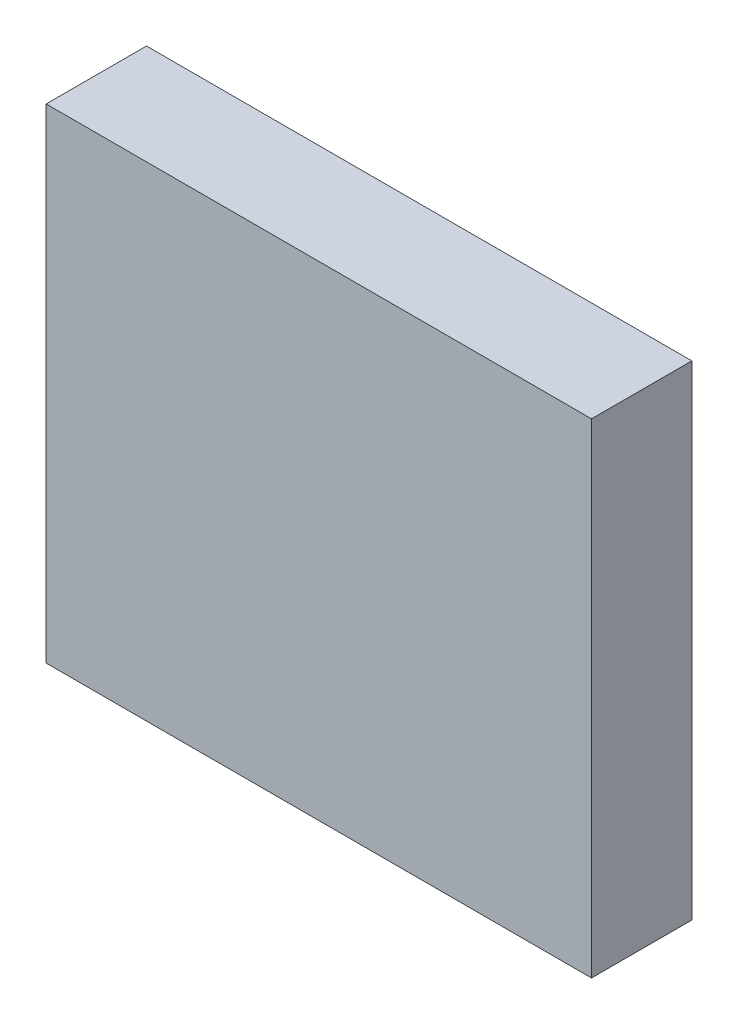
SolidWorks part; units mm, degrees
ref_plane "正面" through (0, 0, 0) normal (0, 0, 1) x (1, 0, 0)
ref_plane "平面" through (0, 0, 0) normal (0, 1, 0) x (1, 0, 0)
ref_plane "右側面" through (0, 0, 0) normal (1, 0, 0) x (0, 0, -1)
sketch "ｽｹｯﾁ1" plane through (0, 0, 0) normal (0, 0, 1) x (1, 0, 0)
  line L0 (-45, 0) -> (45, 0) construction
  line L1 (-45, 45) -> (45, 45)
  line L2 (-45, 45) -> (-45, -45)
  line L3 (-45, -45) -> (45, -45)
  line L4 (45, 45) -> (45, -45)
  line L5 (0, -45) -> (0, 45) construction
  point P8 (0, 0)
  dimension "D1" = 90
  dimension "D2" = 90
  dimension "D3" = 0
  dimension "D4" = 0
extrude "ﾎﾞｽ - 押し出し1" add sketch "ｽｹｯﾁ1" along normal blind 1.6
sketch "ｽｹｯﾁ4" plane through (0, 0, 0) normal (0, 0, -1) x (-1, 0, 0)
  line L0 (-45, -45) -> (-45, 45) construction
  line L1 (-23.89, -36.1) -> (-6.11, -36.1)
  line L2 (-23.89, -36.1) -> (-23.89, -44.6)
  line L3 (-23.89, -44.6) -> (-6.11, -44.6)
  line L4 (-6.11, -36.1) -> (-6.11, -44.6)
  line L6 (45, 45) -> (45, -45) construction
  line L8 (-38.85, 26.89) -> (-36.35, 26.89)
  line L9 (-38.85, 26.89) -> (-38.85, 9.11)
  line L10 (-38.85, 9.11) -> (-36.35, 9.11)
  line L11 (-36.35, 26.89) -> (-36.35, 9.11)
  line L12 (16.11, 44.6) -> (33.89, 44.6)
  line L13 (16.11, 44.6) -> (16.11, 36.1)
  line L14 (16.11, 36.1) -> (33.89, 36.1)
  line L15 (33.89, 44.6) -> (33.89, 36.1)
  line L16 (-45, 45) -> (45, 45) construction
  line L17 (45, -45) -> (-45, -45) construction
  line L18 (36.1, 26.89) -> (44.6, 26.89)
  line L19 (36.1, 26.89) -> (36.1, 9.11)
  line L20 (36.1, 9.11) -> (44.6, 9.11)
  line L21 (44.6, 26.89) -> (44.6, 9.11)
  point P6 (25, 44.6)
  point P7 (-15, -44.6)
  point P14 (-38.85, 18)
  point P15 (-37.6, 9.11)
  point P25 (44.6, 18)
  dimension "D2" = 8.5
  dimension "D3" = 8.5
  dimension "D4" = 17.78
  dimension "D5" = 2.5
  dimension "D6" = 17.78
  dimension "D7" = 27
  dimension "D8" = 7.4
  dimension "D9" = 20
  dimension "D10" = 30
  dimension "D11" = 0.4
  dimension "D12" = 17.78
  dimension "D13" = 17.78
  dimension "D14" = 0.4
  dimension "D15" = 27
  dimension "D16" = 8.5
  dimension "D17" = 0.4
extrude "ﾎﾞｽ - 押し出し2" add sketch "ｽｹｯﾁ4" along normal blind 2.5
sketch "ｽｹｯﾁ5" plane through (0, 0, -2.5) normal (0, 0, -1) x (-1, 0, 0)
  line L8 (-38.85, 9.11) -> (-36.35, 9.11) construction
  line L33 (-37.92, 18.32) -> (-37.28, 18.32)
  line L34 (-37.92, 18.32) -> (-37.92, 17.68)
  line L35 (-37.92, 17.68) -> (-37.28, 17.68)
  line L36 (-37.28, 18.32) -> (-37.28, 17.68)
  line L37 (-38.85, 26.89) -> (-38.85, 9.11) construction
  line L39 (-37.92, 15.78) -> (-37.28, 15.78)
  line L40 (-37.92, 15.78) -> (-37.92, 15.14)
  line L41 (-37.92, 15.14) -> (-37.28, 15.14)
  line L42 (-37.28, 15.78) -> (-37.28, 15.14)
  line L45 (-37.92, 13.24) -> (-37.28, 13.24)
  line L46 (-37.92, 13.24) -> (-37.92, 12.6)
  line L47 (-37.92, 12.6) -> (-37.28, 12.6)
  line L48 (-37.28, 13.24) -> (-37.28, 12.6)
  line L49 (-37.92, 10.7) -> (-37.28, 10.7)
  line L50 (-37.92, 10.7) -> (-37.92, 10.06)
  line L51 (-37.92, 10.06) -> (-37.28, 10.06)
  line L52 (-37.28, 10.7) -> (-37.28, 10.06)
  line L53 (-37.92, 20.86) -> (-37.28, 20.86)
  line L54 (-37.92, 20.86) -> (-37.92, 20.22)
  line L55 (-37.92, 20.22) -> (-37.28, 20.22)
  line L56 (-37.28, 20.86) -> (-37.28, 20.22)
  line L57 (-37.92, 23.4) -> (-37.28, 23.4)
  line L58 (-37.92, 23.4) -> (-37.92, 22.76)
  line L59 (-37.92, 22.76) -> (-37.28, 22.76)
  line L60 (-37.28, 23.4) -> (-37.28, 22.76)
  line L61 (-37.92, 25.94) -> (-37.28, 25.94)
  line L62 (-37.92, 25.94) -> (-37.92, 25.3)
  line L63 (-37.92, 25.3) -> (-37.28, 25.3)
  line L64 (-37.28, 25.94) -> (-37.28, 25.3)
  point P47 (-37.6, 17.68)
  point P50 (-37.6, 9.11)
  point P53 (-37.92, 18)
  point P54 (-38.85, 18)
  point P59 (-37.28, 15.46)
  point P60 (-37.28, 18)
  point P61 (-37.28, 12.92)
  point P70 (-37.28, 10.38)
  point P83 (-37.28, 20.54)
  point P84 (-37.28, 23.08)
  point P85 (-37.28, 25.62)
  point P179 (-37.6, 10.7)
  point P180 (-37.6, 13.24)
  point P181 (-37.6, 15.78)
  point P182 (-37.6, 18.32)
  point P183 (-37.6, 20.86)
  point P184 (-37.6, 23.4)
  point P185 (-37.6, 25.94)
  dimension "D21" = 0.64
  dimension "D22" = 0.64
  dimension "D23" = 0.64
  dimension "D24" = 0.64
  dimension "D25" = 2.54
  dimension "D26" = 0.64
  dimension "D27" = 2.54
  dimension "D28" = 0.64
  dimension "D29" = 2.54
  dimension "D30" = 0.64
  dimension "D31" = 0.64
  dimension "D32" = 0.64
  dimension "D33" = 0.64
  dimension "D34" = 2.54
  dimension "D35" = 2.54
  dimension "D36" = 0.64
  dimension "D37" = 0.64
  dimension "D38" = 0.64
  dimension "D39" = 2.54
  dimension "D40" = 0.64
extrude "ﾎﾞｽ - 押し出し3" add sketch "ｽｹｯﾁ5" along normal blind 6.1
sketch "ｽｹｯﾁ6" plane through (0, 0, 1.6) normal (0, 0, 1) x (1, 0, 0)
  line L0 (-45, -45) -> (45, -45) construction
  line L1 (-41.74, -33.26) -> (-38.26, -33.26)
  line L2 (-41.74, -33.26) -> (-41.74, -36.74)
  line L3 (-41.74, -36.74) -> (-38.26, -36.74)
  line L4 (-38.26, -33.26) -> (-38.26, -36.74)
  line L5 (-45, 45) -> (-45, -45) construction
  line L6 (45, 45) -> (-45, 45) construction
  line L7 (-41.74, 36.74) -> (-38.26, 36.74)
  line L8 (-41.74, 36.74) -> (-41.74, 33.26)
  line L9 (-41.74, 33.26) -> (-38.26, 33.26)
  line L10 (-38.26, 36.74) -> (-38.26, 33.26)
  line L11 (45, -45) -> (45, 45) construction
  line L12 (28.26, -33.26) -> (31.74, -33.26)
  line L13 (28.26, -33.26) -> (28.26, -36.74)
  line L14 (28.26, -36.74) -> (31.74, -36.74)
  line L15 (31.74, -33.26) -> (31.74, -36.74)
  line L17 (28.26, 36.74) -> (31.74, 36.74)
  line L18 (28.26, 36.74) -> (28.26, 33.26)
  line L19 (28.26, 33.26) -> (31.74, 33.26)
  line L20 (31.74, 36.74) -> (31.74, 33.26)
  point P4 (-41.74, -35)
  point P7 (-40, -36.74)
  point P14 (-41.74, 35)
  point P17 (-40, 36.74)
  point P22 (30, -36.74)
  point P25 (31.74, -35)
  point P30 (30, 36.74)
  point P31 (31.74, 35)
  dimension "D1" = 3.48
  dimension "D2" = 3.48
  dimension "D3" = 10
  dimension "D4" = 5
  dimension "D5" = 3.48
  dimension "D6" = 3.48
  dimension "D7" = 10
  dimension "D8" = 5
  dimension "D9" = 15
  dimension "D10" = 10
  dimension "D11" = 3.48
  dimension "D12" = 3.48
  dimension "D13" = 15
  dimension "D14" = 10
  dimension "D15" = 3.48
  dimension "D16" = 3.48
extrude "ﾎﾞｽ - 押し出し4" add sketch "ｽｹｯﾁ6" along normal blind 2
sketch "ｽｹｯﾁ7" plane through (0, 0, 1.6) normal (0, 0, 1) x (1, 0, 0)
  line L0 (-45, -45) -> (45, -45) construction
  line L1 (-41, 2) -> (-39, 2)
  line L2 (-41, 2) -> (-41, -2)
  line L3 (-41, -2) -> (-39, -2)
  line L4 (-39, 2) -> (-39, -2)
  line L5 (-45, 45) -> (-45, -45) construction
  line L6 (45, -45) -> (45, 45) construction
  line L7 (29, 2) -> (31, 2)
  line L8 (29, 2) -> (29, -2)
  line L9 (29, -2) -> (31, -2)
  line L10 (31, 2) -> (31, -2)
  line L11 (45, 45) -> (-45, 45) construction
  line L12 (-7, 36) -> (-3, 36)
  line L13 (-7, 36) -> (-7, 34)
  line L14 (-7, 34) -> (-3, 34)
  line L15 (-3, 36) -> (-3, 34)
  line L17 (-7, -34) -> (-3, -34)
  line L18 (-7, -34) -> (-7, -36)
  line L19 (-7, -36) -> (-3, -36)
  line L20 (-3, -34) -> (-3, -36)
  line L21 (-6, 2) -> (-4, 2)
  line L22 (-6, 2) -> (-6, -2)
  line L23 (-6, -2) -> (-4, -2)
  line L24 (-4, 2) -> (-4, -2)
  point P4 (-41, 0)
  point P7 (-40, -2)
  point P14 (30, 2)
  point P17 (31, 0)
  point P22 (-7, 35)
  point P25 (-5, 36)
  point P30 (-7, -35)
  point P31 (-5, -36)
  point P36 (-4, 0)
  point P37 (29, 0)
  point P38 (-5, 34)
  point P39 (-5, 2)
  dimension "D1" = 4
  dimension "D2" = 2
  dimension "D3" = 45
  dimension "D4" = 5
  dimension "D5" = 4
  dimension "D6" = 2
  dimension "D7" = 15
  dimension "D8" = 45
  dimension "D9" = 4
  dimension "D10" = 2
  dimension "D11" = 10
  dimension "D12" = 40
  dimension "D13" = 4
  dimension "D14" = 2
  dimension "D15" = 10
  dimension "D16" = 40
  dimension "D17" = 4
  dimension "D18" = 2
extrude "ﾎﾞｽ - 押し出し5" add sketch "ｽｹｯﾁ7" along normal blind 1.1
sketch "ｽｹｯﾁ8" plane through (0, 0, 1.6) normal (0, 0, 1) x (1, 0, 0)
  line L1 (7.3, 7.6) -> (14.7, 7.6)
  line L2 (7.3, 7.6) -> (7.3, -7.6)
  line L3 (7.3, -7.6) -> (14.7, -7.6)
  line L4 (14.7, 7.6) -> (14.7, -7.6)
  line L5 (-45, 45) -> (-45, -45) construction
  point P4 (7.3, 0)
  point P11 (-45, 0)
  point P12 (11, 7.6)
  dimension "D1" = 15.2
  dimension "D2" = 7.4
  dimension "D3" = 56
extrude "ﾎﾞｽ - 押し出し6" add sketch "ｽｹｯﾁ8" along normal blind 2.65
sketch "ｽｹｯﾁ9" plane through (0, -44.6, 0) normal (0, -1, 0) x (1, 0, 0)
  line L1 (14.68, -0.93) -> (15.32, -0.93)
  line L2 (14.68, -0.93) -> (14.68, -1.57)
  line L3 (14.68, -1.57) -> (15.32, -1.57)
  line L4 (15.32, -0.93) -> (15.32, -1.57)
  line L5 (6.11, -2.5) -> (6.11, 0) construction
  line L6 (6.11, -1.25) -> (23.89, -1.25) construction
  line L7 (23.89, -2.5) -> (23.89, 0) construction
  line L8 (23.89, -2.5) -> (6.11, -2.5) construction
  line L10 (15, -2.5) -> (15, 0) construction
  line L11 (23.89, 0) -> (6.11, 0) construction
  line L13 (12.14, -0.93) -> (12.78, -0.93)
  line L14 (12.14, -0.93) -> (12.14, -1.57)
  line L15 (12.14, -1.57) -> (12.78, -1.57)
  line L16 (12.78, -0.93) -> (12.78, -1.57)
  line L17 (9.6, -0.93) -> (10.24, -0.93)
  line L18 (9.6, -0.93) -> (9.6, -1.57)
  line L19 (9.6, -1.57) -> (10.24, -1.57)
  line L20 (10.24, -0.93) -> (10.24, -1.57)
  line L21 (7.06, -0.93) -> (7.7, -0.93)
  line L22 (7.06, -0.93) -> (7.06, -1.57)
  line L23 (7.06, -1.57) -> (7.7, -1.57)
  line L24 (7.7, -0.93) -> (7.7, -1.57)
  line L25 (17.22, -0.93) -> (17.86, -0.93)
  line L26 (17.22, -0.93) -> (17.22, -1.57)
  line L27 (17.22, -1.57) -> (17.86, -1.57)
  line L28 (17.86, -0.93) -> (17.86, -1.57)
  line L29 (19.76, -0.93) -> (20.4, -0.93)
  line L30 (19.76, -0.93) -> (19.76, -1.57)
  line L31 (19.76, -1.57) -> (20.4, -1.57)
  line L32 (20.4, -0.93) -> (20.4, -1.57)
  line L33 (22.3, -0.93) -> (22.94, -0.93)
  line L34 (22.3, -0.93) -> (22.3, -1.57)
  line L35 (22.3, -1.57) -> (22.94, -1.57)
  line L36 (22.94, -0.93) -> (22.94, -1.57)
  point P10 (15.32, -1.25)
  point P13 (15, -1.57)
  point P42 (12.46, -1.57)
  point P43 (9.92, -1.57)
  point P44 (12.14, -1.25)
  point P46 (9.6, -1.25)
  point P47 (7.06, -1.25)
  point P48 (7.38, -1.57)
  point P49 (17.54, -1.57)
  point P50 (20.08, -1.57)
  point P51 (22.62, -1.57)
  point P52 (17.22, -1.25)
  point P53 (19.76, -1.25)
  point P54 (22.3, -1.25)
  dimension "D1" = 0.64
  dimension "D2" = 0.64
  dimension "D3" = 0.64
  dimension "D4" = 0.64
  dimension "D5" = 0.64
  dimension "D6" = 0.64
  dimension "D7" = 0.64
  dimension "D8" = 0.64
  dimension "D9" = 0.64
  dimension "D10" = 0.64
  dimension "D11" = 0.64
  dimension "D12" = 2.54
  dimension "D13" = 2.54
  dimension "D14" = 2.54
  dimension "D15" = 0.64
  dimension "D16" = 0.64
  dimension "D17" = 0.64
  dimension "D18" = 2.54
  dimension "D19" = 2.54
  dimension "D20" = 2.54
extrude "ｶｯﾄ - 押し出し1" cut sketch "ｽｹｯﾁ9" against normal blind 7.5
sketch "ｽｹｯﾁ10" plane through (-44.6, 0, 0) normal (-1, 0, 0) x (0, 0, 1)
  line L0 (-1.25, 26.89) -> (-1.25, 9.11) construction
  line L1 (-2.5, 26.89) -> (0, 26.89) construction
  line L2 (-2.5, 9.11) -> (0, 9.11) construction
  line L3 (-2.5, 18) -> (0, 18) construction
  line L4 (-2.5, 9.11) -> (-2.5, 26.89) construction
  line L5 (0, 9.11) -> (0, 26.89) construction
  line L7 (-1.57, 18.32) -> (-0.93, 18.32)
  line L8 (-1.57, 18.32) -> (-1.57, 17.68)
  line L9 (-1.57, 17.68) -> (-0.93, 17.68)
  line L10 (-0.93, 18.32) -> (-0.93, 17.68)
  line L11 (-1.57, 25.94) -> (-0.93, 25.94)
  line L12 (-1.57, 25.94) -> (-1.57, 25.3)
  line L13 (-1.57, 25.3) -> (-0.93, 25.3)
  line L14 (-0.93, 25.94) -> (-0.93, 25.3)
  line L15 (-1.57, 23.4) -> (-0.93, 23.4)
  line L16 (-1.57, 23.4) -> (-1.57, 22.76)
  line L17 (-1.57, 22.76) -> (-0.93, 22.76)
  line L18 (-0.93, 23.4) -> (-0.93, 22.76)
  line L19 (-1.57, 20.86) -> (-0.93, 20.86)
  line L20 (-1.57, 20.86) -> (-1.57, 20.22)
  line L21 (-1.57, 20.22) -> (-0.93, 20.22)
  line L22 (-0.93, 20.86) -> (-0.93, 20.22)
  line L23 (-1.57, 15.78) -> (-0.93, 15.78)
  line L24 (-1.57, 15.78) -> (-1.57, 15.14)
  line L25 (-1.57, 15.14) -> (-0.93, 15.14)
  line L26 (-0.93, 15.78) -> (-0.93, 15.14)
  line L27 (-1.57, 13.24) -> (-0.93, 13.24)
  line L28 (-1.57, 13.24) -> (-1.57, 12.6)
  line L29 (-1.57, 12.6) -> (-0.93, 12.6)
  line L30 (-0.93, 13.24) -> (-0.93, 12.6)
  line L31 (-1.57, 10.7) -> (-0.93, 10.7)
  line L32 (-1.57, 10.7) -> (-1.57, 10.06)
  line L33 (-1.57, 10.06) -> (-0.93, 10.06)
  line L34 (-0.93, 10.7) -> (-0.93, 10.06)
  point P16 (-1.25, 18.32)
  point P17 (-1.57, 18)
  point P30 (-1.57, 20.54)
  point P31 (-0.93, 23.08)
  point P32 (-0.93, 20.54)
  point P33 (-0.93, 25.62)
  point P34 (-1.25, 20.86)
  point P35 (-1.25, 23.4)
  point P36 (-1.25, 25.94)
  point P49 (-0.93, 15.46)
  point P50 (-0.93, 12.92)
  point P51 (-0.93, 10.38)
  dimension "D1" = 0.64
  dimension "D2" = 0.64
  dimension "D3" = 0.64
  dimension "D4" = 0.64
  dimension "D5" = 0.64
  dimension "D6" = 2.54
  dimension "D7" = 2.54
  dimension "D8" = 2.54
  dimension "D9" = 0.64
  dimension "D10" = 0.64
  dimension "D11" = 0.64
  dimension "D12" = 0.64
  dimension "D13" = 0.64
  dimension "D14" = 0.64
  dimension "D15" = 2.54
  dimension "D16" = 2.54
  dimension "D17" = 2.54
  dimension "D18" = 0.64
  dimension "D19" = 0.64
  dimension "D20" = 0.64
extrude "ｶｯﾄ - 押し出し2" cut sketch "ｽｹｯﾁ10" against normal blind 7.5
sketch "ｽｹｯﾁ11" plane through (0, 44.6, 0) normal (0, 1, 0) x (1, 0, 0)
  line L0 (-33.89, 1.25) -> (-16.11, 1.25) construction
  line L1 (-33.89, 2.5) -> (-33.89, 0) construction
  line L2 (-16.11, 2.5) -> (-16.11, 0) construction
  line L3 (-25, 2.5) -> (-25, 0) construction
  line L4 (-33.89, 2.5) -> (-16.11, 2.5) construction
  line L5 (45, 0) -> (-45, 0) construction
  line L7 (-25.32, 1.57) -> (-24.68, 1.57)
  line L8 (-25.32, 1.57) -> (-25.32, 0.93)
  line L9 (-25.32, 0.93) -> (-24.68, 0.93)
  line L10 (-24.68, 1.57) -> (-24.68, 0.93)
  line L11 (-32.94, 1.57) -> (-32.3, 1.57)
  line L12 (-32.94, 1.57) -> (-32.94, 0.93)
  line L13 (-32.94, 0.93) -> (-32.3, 0.93)
  line L14 (-32.3, 1.57) -> (-32.3, 0.93)
  line L15 (-30.4, 1.57) -> (-29.76, 1.57)
  line L16 (-30.4, 1.57) -> (-30.4, 0.93)
  line L17 (-30.4, 0.93) -> (-29.76, 0.93)
  line L18 (-29.76, 1.57) -> (-29.76, 0.93)
  line L19 (-27.86, 1.57) -> (-27.22, 1.57)
  line L20 (-27.86, 1.57) -> (-27.86, 0.93)
  line L21 (-27.86, 0.93) -> (-27.22, 0.93)
  line L22 (-27.22, 1.57) -> (-27.22, 0.93)
  line L23 (-22.78, 1.57) -> (-22.14, 1.57)
  line L24 (-22.78, 1.57) -> (-22.78, 0.93)
  line L25 (-22.78, 0.93) -> (-22.14, 0.93)
  line L26 (-22.14, 1.57) -> (-22.14, 0.93)
  line L27 (-20.24, 1.57) -> (-19.6, 1.57)
  line L28 (-20.24, 1.57) -> (-20.24, 0.93)
  line L29 (-20.24, 0.93) -> (-19.6, 0.93)
  line L30 (-19.6, 1.57) -> (-19.6, 0.93)
  line L31 (-17.7, 1.57) -> (-17.06, 1.57)
  line L32 (-17.7, 1.57) -> (-17.7, 0.93)
  line L33 (-17.7, 0.93) -> (-17.06, 0.93)
  line L34 (-17.06, 1.57) -> (-17.06, 0.93)
  point P16 (-25, 0.93)
  point P17 (-24.68, 1.25)
  point P42 (-27.54, 1.57)
  point P43 (-30.08, 1.57)
  point P44 (-32.62, 1.57)
  point P45 (-32.94, 1.25)
  point P46 (-30.4, 1.25)
  point P47 (-27.86, 1.25)
  point P48 (-22.46, 1.57)
  point P49 (-19.92, 1.57)
  point P50 (-17.38, 1.57)
  point P52 (-22.78, 1.25)
  point P53 (-20.24, 1.25)
  point P54 (-17.7, 1.25)
  dimension "D1" = 0.64
  dimension "D2" = 0.64
  dimension "D3" = 0.64
  dimension "D4" = 0.64
  dimension "D5" = 0.64
  dimension "D6" = 2.54
  dimension "D7" = 2.54
  dimension "D8" = 2.54
  dimension "D9" = 0.64
  dimension "D10" = 0.64
  dimension "D11" = 0.64
  dimension "D12" = 0.64
  dimension "D13" = 0.64
  dimension "D14" = 0.64
  dimension "D15" = 0.64
  dimension "D16" = 0.64
  dimension "D17" = 0.64
  dimension "D18" = 2.54
  dimension "D19" = 2.54
  dimension "D20" = 2.54
extrude "ｶｯﾄ - 押し出し3" cut sketch "ｽｹｯﾁ11" against normal blind 7.5
sketch "ｽｹｯﾁ12" plane through (0, 0, 0) normal (0, 0, -1) x (-1, 0, 0)
  line L7 (45, 45) -> (45, -45) construction
  line L8 (-45, 45) -> (45, 45) construction
  line L9 (45, -45) -> (-45, -45) construction
  line L16 (-45, -45) -> (-45, 45) construction
  line L24 (-23, 30) -> (-24, 31.7321)
  line L25 (-24, 31.7321) -> (-26, 31.7321)
  line L26 (-26, 31.7321) -> (-27, 30)
  line L27 (-27, 30) -> (-26, 28.2679)
  line L28 (-26, 28.2679) -> (-24, 28.2679)
  line L29 (-24, 28.2679) -> (-23, 30)
  line L30 (37, 30) -> (36, 31.7321)
  line L31 (36, 31.7321) -> (34, 31.7321)
  line L32 (34, 31.7321) -> (33, 30)
  line L33 (33, 30) -> (34, 28.2679)
  line L34 (34, 28.2679) -> (36, 28.2679)
  line L35 (36, 28.2679) -> (37, 30)
  line L36 (37, -30) -> (36, -28.2679)
  line L37 (36, -28.2679) -> (34, -28.2679)
  line L38 (34, -28.2679) -> (33, -30)
  line L39 (33, -30) -> (34, -31.7321)
  line L40 (34, -31.7321) -> (36, -31.7321)
  line L41 (36, -31.7321) -> (37, -30)
  line L42 (-23, -30) -> (-24, -28.2679)
  line L43 (-24, -28.2679) -> (-26, -28.2679)
  line L44 (-26, -28.2679) -> (-27, -30)
  line L45 (-27, -30) -> (-26, -31.7321)
  line L46 (-26, -31.7321) -> (-24, -31.7321)
  line L47 (-24, -31.7321) -> (-23, -30)
  circle A0 centre (35, 30) radius 2 construction
  circle A1 centre (35, -30) radius 2 construction
  circle A2 centre (-25, -30) radius 2 construction
  circle A3 centre (-25, 30) radius 2 construction
  dimension "D1" = 10
  dimension "D2" = 15
  dimension "D3" = 15
  dimension "D4" = 10
  dimension "D5" = 15
  dimension "D6" = 20
  dimension "D7" = 20
  dimension "D8" = 15
extrude "ﾎﾞｽ - 押し出し7" add sketch "ｽｹｯﾁ12" along normal blind 3
sketch "ｽｹｯﾁ13" plane through (0, 0, -3) normal (0, 0, -1) x (-1, 0, 0)
  line L0 (-34, 41) -> (-34, 0)
  line L1 (-34, 0) -> (-36, 0)
  line L2 (-36, 0) -> (-36, -39)
  line L3 (-36, -39) -> (5, -39)
  line L4 (5, -39) -> (5, -41)
  line L5 (5, -41) -> (44, -41)
  line L6 (44, -41) -> (44, 0)
  line L7 (44, 0) -> (46, 0)
  line L8 (46, 0) -> (46, 39)
  line L9 (46, 39) -> (5, 39)
  line L10 (5, 39) -> (5, 41)
  line L11 (5, 41) -> (-34, 41)
  line L12 (5, -57.6044) -> (5, 50.3983) construction
  line L13 (45, 45) -> (45, -45) construction
  line L14 (-24, 31.7321) -> (-26, 31.7321) construction
  line L15 (-24, -28.2679) -> (-26, -28.2679) construction
  line L16 (36, -28.2679) -> (34, -28.2679) construction
  line L18 (36, 31.7321) -> (34, 31.7321) construction
  circle A0 centre (-25, 30) radius 1
  circle A1 centre (-25, -30) radius 1
  circle A2 centre (35, -30) radius 1
  circle A3 centre (35, 30) radius 1
  point P26 (-25, 31.7321)
  point P30 (-25, -28.2679)
  point P38 (35, -28.2679)
  point P46 (35, 31.7321)
  dimension "D1" = 41
  dimension "D2" = 39
  dimension "D3" = 41
  dimension "D4" = 39
  dimension "D5" = 41
  dimension "D6" = 39
  dimension "D7" = 41
  dimension "D8" = 39
  dimension "D9" = 40
extrude "ﾎﾞｽ - 押し出し8" add sketch "ｽｹｯﾁ13" along normal blind 2 separate body
sketch "ｽｹｯﾁ14" plane through (0, 0, -2.5) normal (0, 0, -1) x (-1, 0, 0)
  line L6 (46.35, 45) -> (-55, 45)
  line L7 (46.35, 45) -> (46.35, -45)
  line L8 (46.35, -45) -> (-55, -45)
  line L9 (-55, 45) -> (-55, -45)
  point P5 (46.35, 0)
  dimension "D1" = 46.35
  dimension "D2" = 90
  dimension "D3" = 55
extrude "ﾎﾞｽ - 押し出し9" add sketch "ｽｹｯﾁ14" against normal blind 18.65 separate body
